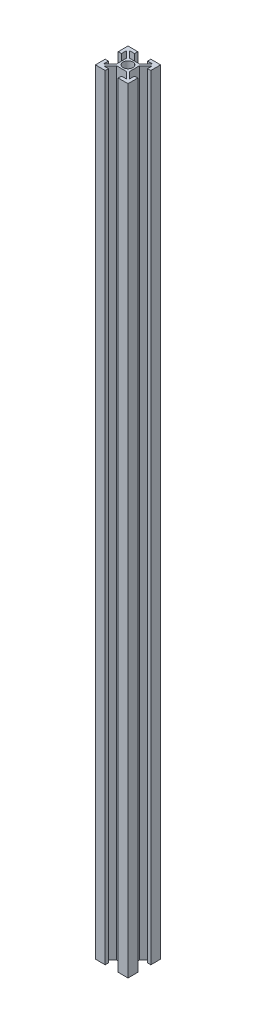
SolidWorks part; units mm, degrees
material "1060 Alloy"
ref_plane "Front Plane" through (0, 0, 0) normal (0, 0, 1) x (1, 0, 0)
ref_plane "Top Plane" through (0, 0, 0) normal (0, 1, 0) x (1, 0, 0)
ref_plane "Right Plane" through (0, 0, 0) normal (1, 0, 0) x (0, 0, -1)
sketch "Sketch1" plane through (0, 0, 0) normal (0, 0, 1) x (1, 0, 0)
  line L0 (18.2498, -12.1687) -> (243.1097, 212.6913) construction
  line L1 (243.1097, 212.6913) -> (18.2498, 437.5512) construction
  dimension "D1" = 318
  dimension "D2" = 318
  dimension "D3" = 90
sketch "2020 sketch" plane through (0, 0, 0) normal (0, 1, 0) x (1, 0, 0)
  line L0 (-4, 10) -> (-4, 8)
  line L1 (-10, 10) -> (-4, 10)
  line L2 (-10, 10) -> (-10, 4)
  line L3 (-10, -10) -> (-4, -10)
  line L4 (10, 10) -> (10, 4)
  line L5 (-10, 10) -> (10, -10) construction
  line L6 (-10, -10) -> (10, 10) construction
  line L7 (-4, 8) -> (-7, 8)
  line L8 (-7, 8) -> (-3, 4)
  line L9 (-3, 4) -> (3, 4)
  line L10 (3, 4) -> (7, 8)
  line L11 (7, 8) -> (4, 8)
  line L12 (4, 8) -> (4, 10)
  line L13 (4, 3) -> (4, -3)
  line L14 (8, 7) -> (4, 3)
  line L15 (8, 4) -> (8, 7)
  line L16 (10, 4) -> (8, 4)
  line L17 (8, -4) -> (10, -4)
  line L18 (8, -7) -> (8, -4)
  line L19 (4, -3) -> (8, -7)
  line L20 (3, -4) -> (-3, -4)
  line L21 (7, -8) -> (3, -4)
  line L22 (4, -8) -> (7, -8)
  line L23 (4, -10) -> (4, -8)
  line L24 (-4, -8) -> (-4, -10)
  line L25 (-7, -8) -> (-4, -8)
  line L26 (-3, -4) -> (-7, -8)
  line L27 (-4, -3) -> (-4, 3)
  line L28 (-8, -7) -> (-4, -3)
  line L29 (-8, -4) -> (-8, -7)
  line L30 (-10, -4) -> (-8, -4)
  line L31 (-8, 4) -> (-10, 4)
  line L32 (-8, 7) -> (-8, 4)
  line L33 (-4, 3) -> (-8, 7)
  line L34 (-10, -4) -> (-10, -10)
  line L35 (10, -4) -> (10, -10)
  line L36 (4, 10) -> (10, 10)
  line L37 (4, -10) -> (10, -10)
  circle A0 centre (0, 0) radius 3
  point P0 (0, 0)
  point P14 (4, 9)
  point P42 (0, 0)
  dimension "D9" = 6
  dimension "D1" = 20
  dimension "D2" = 20
  dimension "D3" = 8
  dimension "D4" = 6
  dimension "D5" = 6
  dimension "D6" = 2
  dimension "D7" = 4
  dimension "D8" = 4
extrude "Boss-Extrude1" add sketch "2020 sketch" along normal blind 475 from vertex at -12.1687 contours A0 | L28 L27 L33 L32 L31 L2 L1 L0 L7 L8 L9 L10 L11 L12 L36 L4 L16 L15 L14 L13 L19 L18 L17 L35 L37 L23 L22 L21 L20 L26 L25 L24 L3 L34 L30 L29
